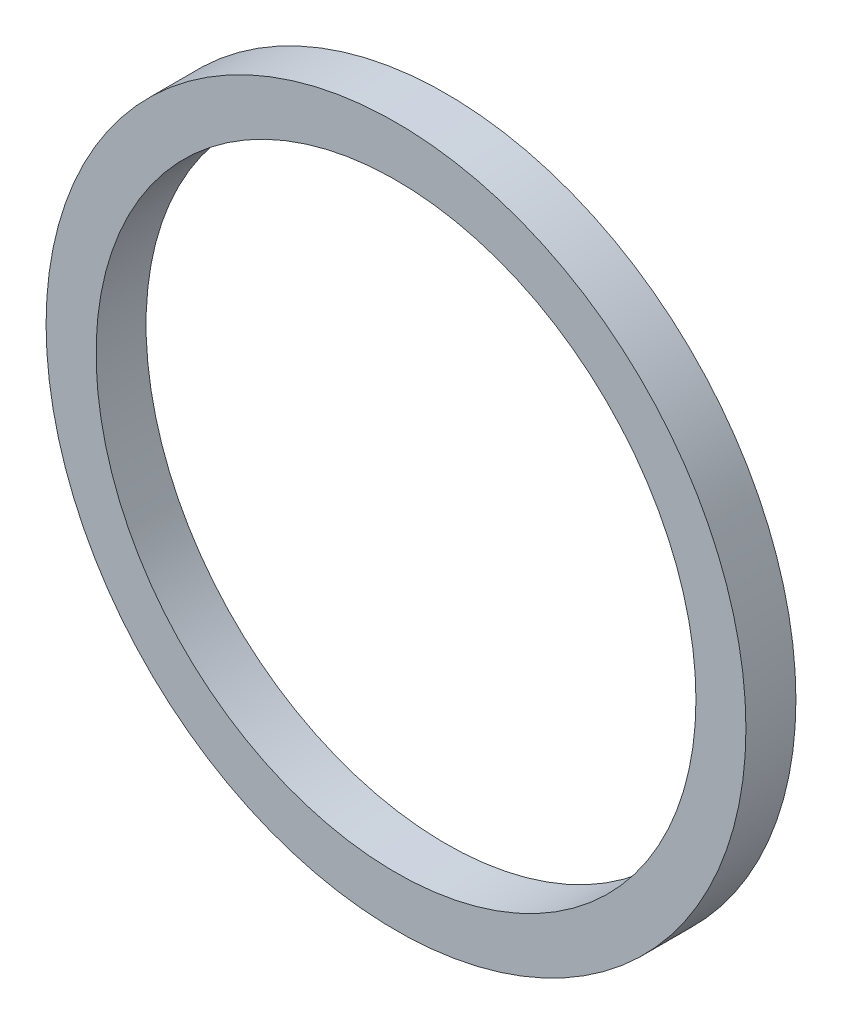
SolidWorks part; units mm, degrees
ref_plane "Front Plane" through (0, 0, 0) normal (0, 0, 1) x (1, 0, 0)
ref_plane "Top Plane" through (0, 0, 0) normal (0, 1, 0) x (1, 0, 0)
ref_plane "Right Plane" through (0, 0, 0) normal (1, 0, 0) x (0, 0, -1)
sketch "Sketch2" plane through (0, 0, 0) normal (0, 0, 1) x (1, 0, 0)
  circle A0 centre (0, 0) radius 35
  dimension "D1" = 70
extrude "Boss-Extrude1" add sketch "Sketch2" along normal mid plane 5
sketch "Sketch3" plane through (0, 0, 2.5) normal (0, 0, 1) x (1, 0, 0)
  circle A0 centre (0, 0) radius 30
  dimension "D1" = 60
extrude "Cut-Extrude1" cut sketch "Sketch3" against normal through all contours A0
